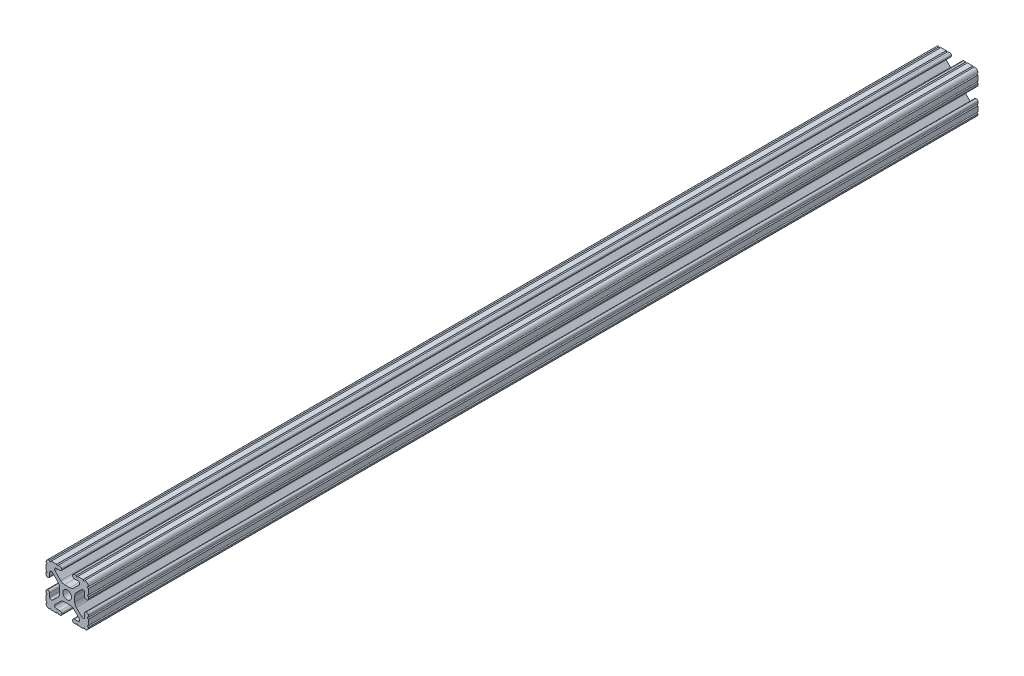
SolidWorks part; units mm, degrees
ref_plane "Front Plane" through (0, 0, 0) normal (0, 0, 1) x (1, 0, 0)
ref_plane "Top Plane" through (0, 0, 0) normal (0, 1, 0) x (1, 0, 0)
ref_plane "Right Plane" through (0, 0, 0) normal (1, 0, 0) x (0, 0, -1)
sketch "Sketch1" plane through (0, 0, 0) normal (0, 0, 1) x (1, 0, 0)
  line L88 (-7.1797, -8.6452) -> (-3.9523, -5.4237)
  line L89 (-1.7093, -4.4958) -> (1.7093, -4.4958)
  line L90 (3.9523, -5.4237) -> (7.1797, -8.6452)
  line L91 (6.4164, -10.4902) -> (4.2875, -10.4902)
  line L92 (3.2385, -11.5392) -> (3.2385, -11.651)
  line L93 (4.2875, -12.7) -> (5.3171, -12.7)
  line L94 (6.3331, -12.7) -> (9.5504, -12.7)
  line L95 (12.7, -9.5504) -> (12.7, -6.3331)
  line L96 (12.7, -5.3171) -> (12.7, -4.2875)
  line L97 (11.651, -3.2385) -> (11.5392, -3.2385)
  line L98 (10.4902, -4.2875) -> (10.4902, -6.4021)
  line L99 (8.7371, -7.1294) -> (5.441, -3.8408)
  line L100 (4.5085, -1.5932) -> (4.5085, 1.5932)
  line L101 (5.441, 3.8408) -> (8.7371, 7.1294)
  line L102 (10.4902, 6.4021) -> (10.4902, 4.2875)
  line L103 (11.5392, 3.2385) -> (11.651, 3.2385)
  line L104 (12.7, 4.2875) -> (12.7, 5.3171)
  line L105 (12.7, 6.3331) -> (12.7, 9.5504)
  line L106 (9.5504, 12.7) -> (6.3331, 12.7)
  line L107 (5.3171, 12.7) -> (4.2875, 12.7)
  line L108 (3.2385, 11.651) -> (3.2385, 11.5392)
  line L109 (4.2875, 10.4902) -> (6.4768, 10.4902)
  line L110 (7.207, 8.7244) -> (3.8983, 5.4232)
  line L111 (1.6558, 4.4958) -> (-1.6558, 4.4958)
  line L112 (-3.8983, 5.4232) -> (-7.207, 8.7244)
  line L113 (-6.4768, 10.4902) -> (-4.2875, 10.4902)
  line L114 (-3.2385, 11.5392) -> (-3.2385, 11.651)
  line L115 (-4.2875, 12.7) -> (-5.3171, 12.7)
  line L116 (-6.3331, 12.7) -> (-9.5504, 12.7)
  line L117 (-12.7, 9.5504) -> (-12.7, 6.3331)
  line L118 (-12.7, 5.3171) -> (-12.7, 4.2875)
  line L119 (-11.651, 3.2385) -> (-11.5392, 3.2385)
  line L120 (-10.4902, 4.2875) -> (-10.4902, 6.4021)
  line L121 (-8.7371, 7.1294) -> (-5.441, 3.8408)
  line L122 (-4.5085, 1.5932) -> (-4.5085, -1.5932)
  line L123 (-5.441, -3.8408) -> (-8.7371, -7.1294)
  line L124 (-10.4902, -6.4021) -> (-10.4902, -4.2875)
  line L125 (-11.5392, -3.2385) -> (-11.651, -3.2385)
  line L126 (-12.7, -4.2875) -> (-12.7, -5.3171)
  line L127 (-12.7, -6.3331) -> (-12.7, -9.5504)
  line L128 (-9.5504, -12.7) -> (-6.3331, -12.7)
  line L129 (-5.3171, -12.7) -> (-4.2875, -12.7)
  line L130 (-3.2385, -11.651) -> (-3.2385, -11.5392)
  line L131 (-4.2875, -10.4902) -> (-6.4164, -10.4902)
  circle A1 centre (0, 0) radius 2.6035
  arc A104 (-7.1797, -8.6452) -> (-6.4164, -10.4902) centre (-6.4164, -9.4098) ccw
  arc A105 (-1.7093, -4.4958) -> (-3.9523, -5.4237) centre (-1.7093, -7.6708) ccw
  arc A106 (3.9523, -5.4237) -> (1.7093, -4.4958) centre (1.7093, -7.6708) ccw
  arc A107 (6.4164, -10.4902) -> (7.1797, -8.6452) centre (6.4164, -9.4098) ccw
  arc A108 (4.2875, -10.4902) -> (3.2385, -11.5392) centre (4.2875, -11.5392) ccw
  arc A109 (3.2385, -11.651) -> (4.2875, -12.7) centre (4.2875, -11.651) ccw
  arc A110 (6.3331, -12.7) -> (5.3171, -12.7) centre (5.8251, -12.7) ccw
  arc A111 (10.5664, -12.6998) -> (9.5504, -12.7) centre (10.0584, -12.7) ccw
  arc A112 (10.5664, -12.6998) -> (12.6998, -10.5664) centre (10.5918, -10.5918) ccw
  arc A113 (12.7, -9.5504) -> (12.6998, -10.5664) centre (12.7, -10.0584) ccw
  arc A114 (12.7, -5.3171) -> (12.7, -6.3331) centre (12.7, -5.8251) ccw
  arc A115 (12.7, -4.2875) -> (11.651, -3.2385) centre (11.651, -4.2875) ccw
  arc A116 (11.5392, -3.2385) -> (10.4902, -4.2875) centre (11.5392, -4.2875) ccw
  arc A117 (8.7371, -7.1294) -> (10.4902, -6.4021) centre (9.4628, -6.4021) ccw
  arc A118 (4.5085, -1.5932) -> (5.441, -3.8408) centre (7.6835, -1.5932) ccw
  arc A119 (5.441, 3.8408) -> (4.5085, 1.5932) centre (7.6835, 1.5932) ccw
  arc A120 (10.4902, 6.4021) -> (8.7371, 7.1294) centre (9.4628, 6.4021) ccw
  arc A121 (10.4902, 4.2875) -> (11.5392, 3.2385) centre (11.5392, 4.2875) ccw
  arc A122 (11.651, 3.2385) -> (12.7, 4.2875) centre (11.651, 4.2875) ccw
  arc A123 (12.7, 6.3331) -> (12.7, 5.3171) centre (12.7, 5.8251) ccw
  arc A124 (12.6998, 10.5664) -> (12.7, 9.5504) centre (12.7, 10.0584) ccw
  arc A125 (12.6998, 10.5664) -> (10.5664, 12.6998) centre (10.5918, 10.5918) ccw
  arc A126 (9.5504, 12.7) -> (10.5664, 12.6998) centre (10.0584, 12.7) ccw
  arc A127 (5.3171, 12.7) -> (6.3331, 12.7) centre (5.8251, 12.7) ccw
  arc A128 (4.2875, 12.7) -> (3.2385, 11.651) centre (4.2875, 11.651) ccw
  arc A129 (3.2385, 11.5392) -> (4.2875, 10.4902) centre (4.2875, 11.5392) ccw
  arc A130 (7.207, 8.7244) -> (6.4768, 10.4902) centre (6.4768, 9.4563) ccw
  arc A131 (1.6558, 4.4958) -> (3.8983, 5.4232) centre (1.6558, 7.6708) ccw
  arc A132 (-3.8983, 5.4232) -> (-1.6558, 4.4958) centre (-1.6558, 7.6708) ccw
  arc A133 (-6.4768, 10.4902) -> (-7.207, 8.7244) centre (-6.4768, 9.4563) ccw
  arc A134 (-4.2875, 10.4902) -> (-3.2385, 11.5392) centre (-4.2875, 11.5392) ccw
  arc A135 (-3.2385, 11.651) -> (-4.2875, 12.7) centre (-4.2875, 11.651) ccw
  arc A136 (-6.3331, 12.7) -> (-5.3171, 12.7) centre (-5.8251, 12.7) ccw
  arc A137 (-10.5664, 12.6998) -> (-9.5504, 12.7) centre (-10.0584, 12.7) ccw
  arc A138 (-10.5664, 12.6998) -> (-12.6998, 10.5664) centre (-10.5918, 10.5918) ccw
  arc A139 (-12.7, 9.5504) -> (-12.6998, 10.5664) centre (-12.7, 10.0584) ccw
  arc A140 (-12.7, 5.3171) -> (-12.7, 6.3331) centre (-12.7, 5.8251) ccw
  arc A141 (-12.7, 4.2875) -> (-11.651, 3.2385) centre (-11.651, 4.2875) ccw
  arc A142 (-11.5392, 3.2385) -> (-10.4902, 4.2875) centre (-11.5392, 4.2875) ccw
  arc A143 (-8.7371, 7.1294) -> (-10.4902, 6.4021) centre (-9.4628, 6.4021) ccw
  arc A144 (-4.5085, 1.5932) -> (-5.441, 3.8408) centre (-7.6835, 1.5932) ccw
  arc A145 (-5.441, -3.8408) -> (-4.5085, -1.5932) centre (-7.6835, -1.5932) ccw
  arc A146 (-10.4902, -6.4021) -> (-8.7371, -7.1294) centre (-9.4628, -6.4021) ccw
  arc A147 (-10.4902, -4.2875) -> (-11.5392, -3.2385) centre (-11.5392, -4.2875) ccw
  arc A148 (-11.651, -3.2385) -> (-12.7, -4.2875) centre (-11.651, -4.2875) ccw
  arc A149 (-12.7, -6.3331) -> (-12.7, -5.3171) centre (-12.7, -5.8251) ccw
  arc A150 (-12.6998, -10.5664) -> (-12.7, -9.5504) centre (-12.7, -10.0584) ccw
  arc A151 (-12.6998, -10.5664) -> (-10.5664, -12.6998) centre (-10.5918, -10.5918) ccw
  arc A152 (-9.5504, -12.7) -> (-10.5664, -12.6998) centre (-10.0584, -12.7) ccw
  arc A153 (-5.3171, -12.7) -> (-6.3331, -12.7) centre (-5.8251, -12.7) ccw
  arc A154 (-4.2875, -12.7) -> (-3.2385, -11.651) centre (-4.2875, -11.651) ccw
  arc A155 (-3.2385, -11.5392) -> (-4.2875, -10.4902) centre (-4.2875, -11.5392) ccw
extrude "Boss-Extrude1" add sketch "Sketch1" along normal mid plane 533.4
